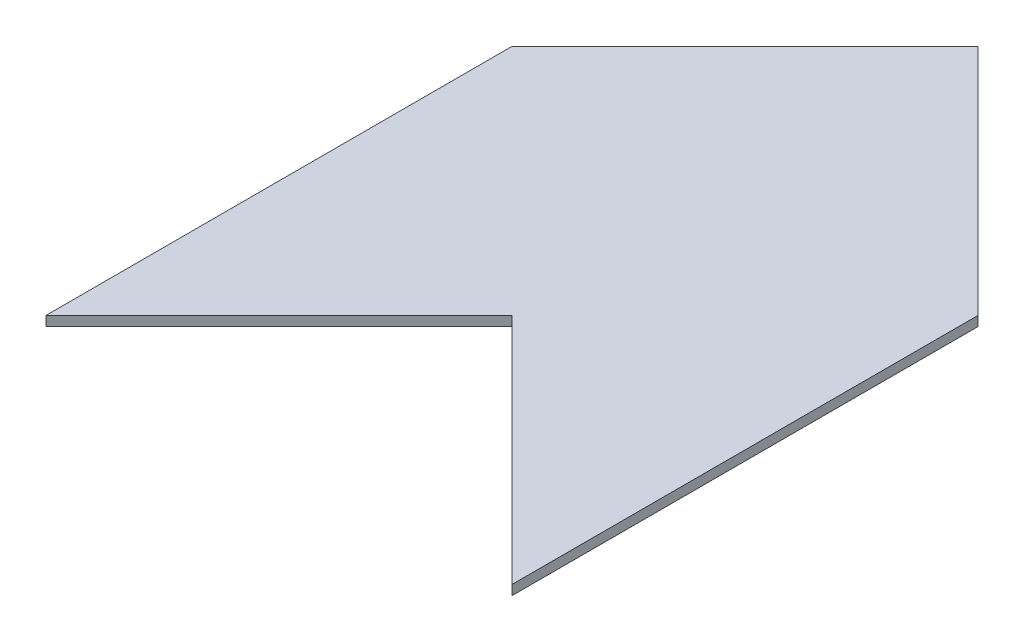
SolidWorks part; units mm, degrees
ref_plane "Front Plane" through (0, 0, 0) normal (0, 0, 1) x (1, 0, 0)
ref_plane "Top Plane" through (0, 0, 0) normal (0, 1, 0) x (1, 0, 0)
ref_plane "Right Plane" through (0, 0, 0) normal (1, 0, 0) x (0, 0, -1)
sketch "Sketch1" plane through (0, 0, 0) normal (0, 1, 0) x (1, 0, 0)
  line L0 (0, 0) -> (0, 199504.4365) construction
  line L1 (0, 0) -> (76.2, -76.2)
  line L2 (76.2, -76.2) -> (76.2, 76.2)
  line L3 (76.2, 76.2) -> (0, 152.4)
  line L4 (0, 0) -> (-76.2, -76.2)
  line L5 (-76.2, -76.2) -> (-76.2, 76.2)
  line L6 (-76.2, 76.2) -> (0, 152.4)
  dimension "D1" = 152.4
  dimension "D2" = 76.2
  dimension "D3" = 76.2
  dimension "D4" = 76.2
extrude "Boss-Extrude1" add sketch "Sketch1" along normal blind 3.175
